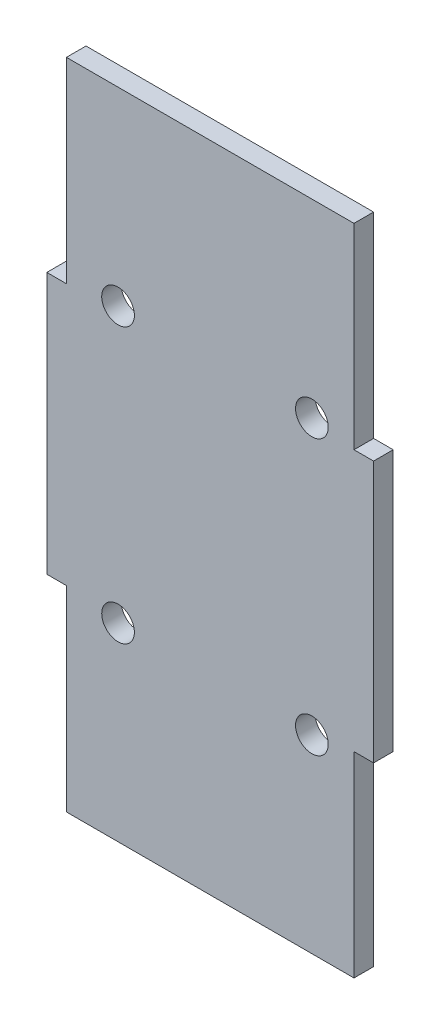
SolidWorks part; units mm, degrees
ref_plane "Front Plane" through (0, 0, 0) normal (0, 0, 1) x (1, 0, 0)
ref_plane "Top Plane" through (0, 0, 0) normal (0, 1, 0) x (1, 0, 0)
ref_plane "Right Plane" through (0, 0, 0) normal (1, 0, 0) x (0, 0, -1)
sketch "Sketch1" plane through (0, 0, 0) normal (0, 0, 1) x (1, 0, 0)
  line L0 (-25, 9.2754) -> (-22, 9.2754)
  line L1 (22, -60.7246) -> (-22, -60.7246)
  line L2 (25, -30.7246) -> (25, 9.2754)
  line L3 (22, 39.2754) -> (-22, 39.2754)
  line L4 (-25, -30.7246) -> (-25, 9.2754)
  line L5 (22, -61.6) -> (-22, 61.6) construction
  line L6 (22, 61.6) -> (-22, -61.6) construction
  line L7 (-25, -10.7246) -> (25, -10.7246) construction
  line L8 (-22, -30.7246) -> (-25, -30.7246)
  line L9 (25, 9.2754) -> (22, 9.2754)
  line L11 (22, -30.7246) -> (25, -30.7246)
  line L12 (-22, 9.2754) -> (-22, 39.2754)
  line L13 (-22, -30.7246) -> (-22, -60.7246)
  line L14 (22, -30.7246) -> (22, -60.7246)
  line L15 (22, 9.2754) -> (22, 39.2754)
  circle A0 centre (15.559, 10.2754) radius 2.5
  circle A1 centre (-14.0986, 10.2754) radius 2.5
  circle A2 centre (15.559, -31.7246) radius 2.5
  circle A3 centre (-14.0986, -31.7246) radius 2.5
  point P0 (0, 0)
  point P4 (-23.5, -30.7246)
  point P25 (0, 0)
  dimension "D6" = 5
  dimension "D1" = 100
  dimension "D2" = 50
  dimension "D3" = 40
  dimension "D4" = 30
  dimension "D5" = 40
  dimension "D7" = 42
extrude "Boss-Extrude1" add sketch "Sketch1" along normal blind 3
